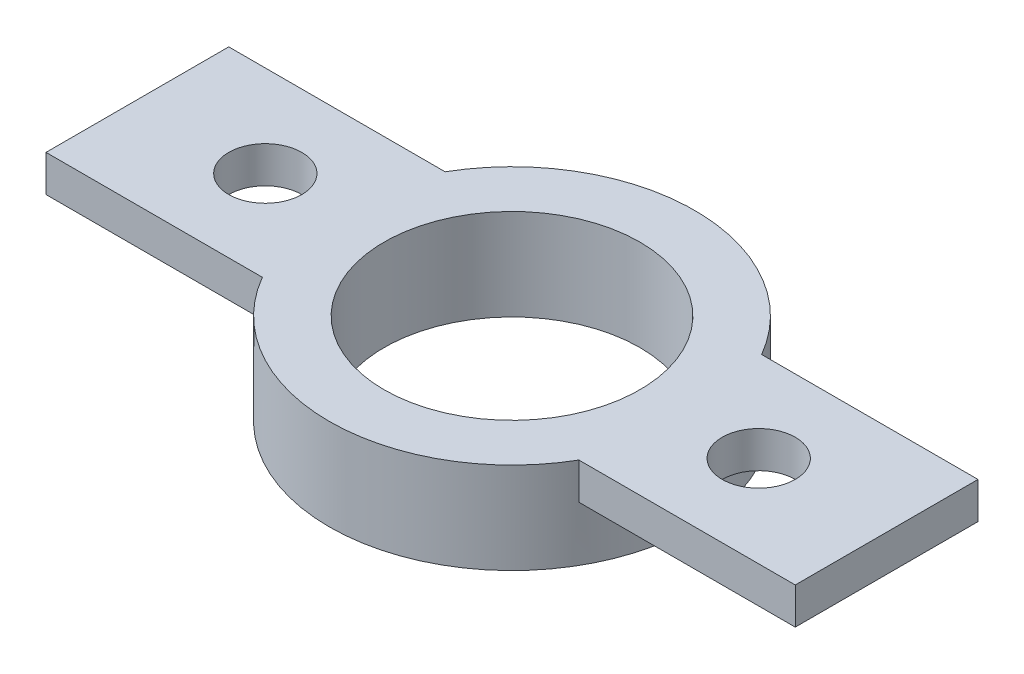
SolidWorks part; units mm, degrees
ref_plane "Front" through (0, 0, 0) normal (0, 0, 1) x (1, 0, 0)
ref_plane "Top" through (0, 0, 0) normal (0, 1, 0) x (1, 0, 0)
ref_plane "Right" through (0, 0, 0) normal (1, 0, 0) x (0, 0, -1)
sketch "Sketch1" plane through (0, 0, 0) normal (0, 1, 0) x (1, 0, 0)
  line L1 (0, 0) -> (35, 0)
  line L2 (0, 0) -> (0, 10)
  line L3 (0, 10) -> (35, 10)
  line L4 (35, 0) -> (35, 10)
  dimension "D1" = 35
  dimension "D2" = 10
extrude "Boss-Extrude1" add sketch "Sketch1" along normal blind 2
sketch "Sketch2" plane through (0, 2, 0) normal (0, 1, 0) x (1, 0, 0)
  line L0 (0, 10) -> (0, 0) construction
  line L2 (0, 0) -> (35, 0) construction
  circle A0 centre (17.5, 5) radius 10
  dimension "D1" = 17.5
  dimension "D2" = 5
extrude "Boss-Extrude2" add sketch "Sketch2" against normal blind 5
sketch "Sketch3" plane through (0, 2, 0) normal (0, 1, 0) x (1, 0, 0)
  circle A0 centre (17.5, 5) radius 7
extrude "Cut-Extrude1" cut sketch "Sketch3" against normal blind 2000
sketch "Sketch4" plane through (0, 0, 0) normal (0, -1, 0) x (1, 0, 0)
  line L0 (0, -10) -> (0, 0) construction
  line L1 (35, 0) -> (35, -10) construction
  line L2 (0, 0) -> (8.8397, 0) construction
  line L5 (26.1603, 0) -> (35, 0) construction
  circle A0 centre (4, -5) radius 2
  circle A1 centre (31, -5) radius 2
  dimension "D1" = 4
  dimension "D2" = 4
  dimension "D3" = 5
  dimension "D4" = 5
extrude "Cut-Extrude2" cut sketch "Sketch4" against normal blind 20
sketch "Sketch5" plane through (0, 0, 0) normal (-1, 0, 0) x (0, 0, 1)
  line L1 (0, 2) -> (-10, 2)
  line L2 (0, 2) -> (0, 0)
  line L3 (0, 0) -> (-10, 0)
  line L4 (-10, 2) -> (-10, 0)
extrude "Boss-Extrude3" add sketch "Sketch5" along normal blind 3
sketch "Sketch6" plane through (35, 0, 0) normal (1, 0, 0) x (0, 0, -1)
  line L1 (0, 0) -> (10, 0)
  line L2 (0, 0) -> (0, 2)
  line L3 (0, 2) -> (10, 2)
  line L4 (10, 0) -> (10, 2)
extrude "Boss-Extrude4" add sketch "Sketch6" along normal blind 3
